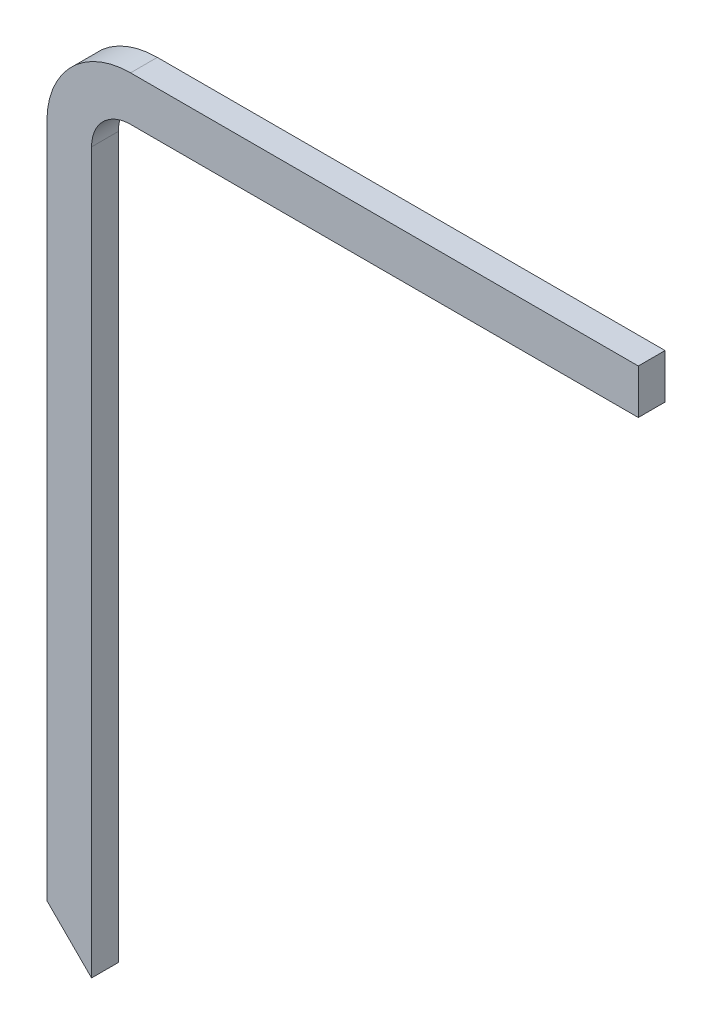
SolidWorks part; units mm, degrees
ref_plane "Alzado" through (0, 0, 0) normal (0, 0, 1) x (1, 0, 0)
ref_plane "Planta" through (0, 0, 0) normal (0, 1, 0) x (1, 0, 0)
ref_plane "Vista lateral" through (0, 0, 0) normal (1, 0, 0) x (0, 0, -1)
sketch "Croquis1" plane through (0, 0, 0) normal (0, 0, 1) x (1, 0, 0)
  line L4 (0, 0) -> (-10, 10) construction
  line L5 (122.5, 170) -> (122.5, 180) construction
  line L6 (122.5, 180) -> (8.736, 180)
  line L7 (-10, 161.264) -> (-10, 10)
  line L8 (-10, 10) -> (0, 0)
  line L9 (0, 0) -> (0, 161.264)
  line L10 (8.736, 170) -> (122.5, 170)
  line L11 (122.5, 170) -> (122.5, 180)
  arc A1 (8.736, 180) -> (-10, 161.264) centre (8.736, 161.264) ccw
  arc A2 (0, 161.264) -> (8.736, 170) centre (8.736, 161.264) cw
  point P3 (0, 0)
  dimension "D3" = 180
  dimension "D6" = 18.736
  dimension "D7" = 8.736
  dimension "D1" = 10
  dimension "D2" = 132.5
  dimension "D4" = 14.1421
  dimension "D5" = 170
extrude "Saliente-Extruir1" add sketch "Croquis1" along normal blind 6
